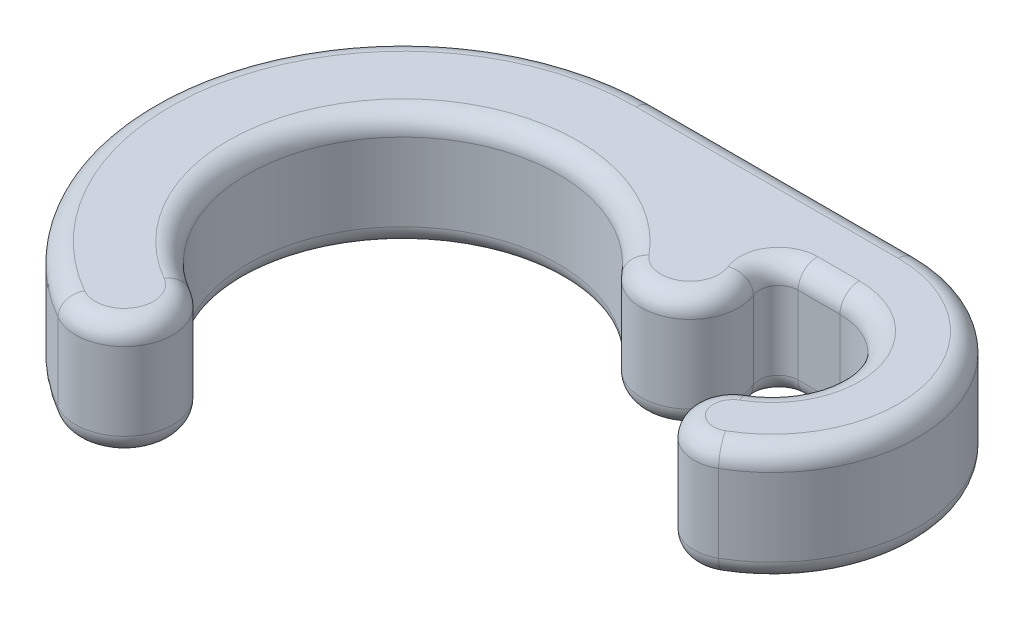
SolidWorks part; units mm, degrees
material "ABS"
ref_plane "Front Plane" through (0, 0, 0) normal (0, 0, 1) x (1, 0, 0)
ref_plane "Top Plane" through (0, 0, 0) normal (0, 1, 0) x (1, 0, 0)
ref_plane "Right Plane" through (0, 0, 0) normal (1, 0, 0) x (0, 0, -1)
sketch "Sketch1" plane through (0, 0, 0) normal (0, 1, 0) x (1, 0, 0)
  line L0 (-3.8669, 2.75) -> (6.75, 2.75) construction
  line L1 (0, 6.5) -> (6.75, 6.5) construction
  line L2 (6.75, 2.75) -> (8.125, 0.3684) construction
  line L3 (6.75, 4.5) -> (4.6904, 4.5)
  line L4 (6.5, 0.866) -> (6.5, 4.5) construction
  line L5 (6.75, 6.5) -> (0, 6.5)
  line L6 (0, 0) -> (-2.625, -4.5466) construction
  line L7 (0, 0) -> (4.0506, 3.34) construction
  line L8 (0, 0) -> (9.0933, -5.25) construction
  line L9 (11.0933, -1.7859) -> (2, 3.4641) construction
  line L10 (7.0933, -8.7141) -> (-2, -3.4641) construction
  line L11 (4.6904, 4.5) -> (0.2228, 4.5) construction
  line L12 (-3.25, -5.6292) -> (-2.625, -4.5466) construction
  line L13 (4.0506, 3.34) -> (5.015, 4.1352) construction
  arc A0 (3.0861, 2.5447) -> (-2, -3.4641) centre (0, 0) ccw
  arc A1 (0, 6.5) -> (-3.25, -5.6292) centre (0, 0) ccw
  arc A2 (7.625, 1.2345) -> (6.75, 4.5) centre (6.75, 2.75) ccw
  arc A3 (8.625, -0.4976) -> (6.75, 6.5) centre (6.75, 2.75) ccw
  arc A4 (7.625, 1.2345) -> (8.625, -0.4976) centre (8.125, 0.3684) ccw
  arc A5 (-3.25, -5.6292) -> (-2, -3.4641) centre (-2.625, -4.5466) ccw
  circle A6 centre (0, 0) radius 6.5 construction
  circle A7 centre (9.0933, -5.25) radius 4 construction
  arc A8 (5.015, 4.1352) -> (4.6904, 4.5) centre (0, 0) ccw
  arc A9 (3.0861, 2.5447) -> (5.015, 4.1352) centre (4.0506, 3.34) ccw
  dimension "D1" = 8
  dimension "D2" = 2.5
  dimension "D3" = 2
  dimension "D4" = 3.5
  dimension "D6" = 0.25
  dimension "D5" = 60
  dimension "D7" = 60
extrude "Boss-Extrude1" add sketch "Sketch1" along normal blind 3
fillet "Fillet1" radius 0.5 1 edges at (4.6904, 1.5, -4.5)
fillet "Fillet2" radius 0.5 20 edges at (5.2564, 0, -4.279) (6.2107, 0, -4.5) (8.4404, 0, -3.2029) (7.259, 0, 0.1316) (10.3722, 0, -3.7206) (3.375, 0, -6.5) (-6.2785, 0, -1.6823) (-1.5425, 0, 5.1716) (-3.0531, 0, -2.5843) (4.6912, 0, -2.2666) (-3.0531, 3, -2.5843) (-1.5425, 3, 5.1716) (-6.2785, 3, -1.6823) (3.375, 3, -6.5) (10.3722, 3, -3.7206) (7.259, 3, 0.1316) (8.4404, 3, -3.2029) (6.2107, 3, -4.5) (5.2564, 3, -4.279) (4.6912, 3, -2.2666)
